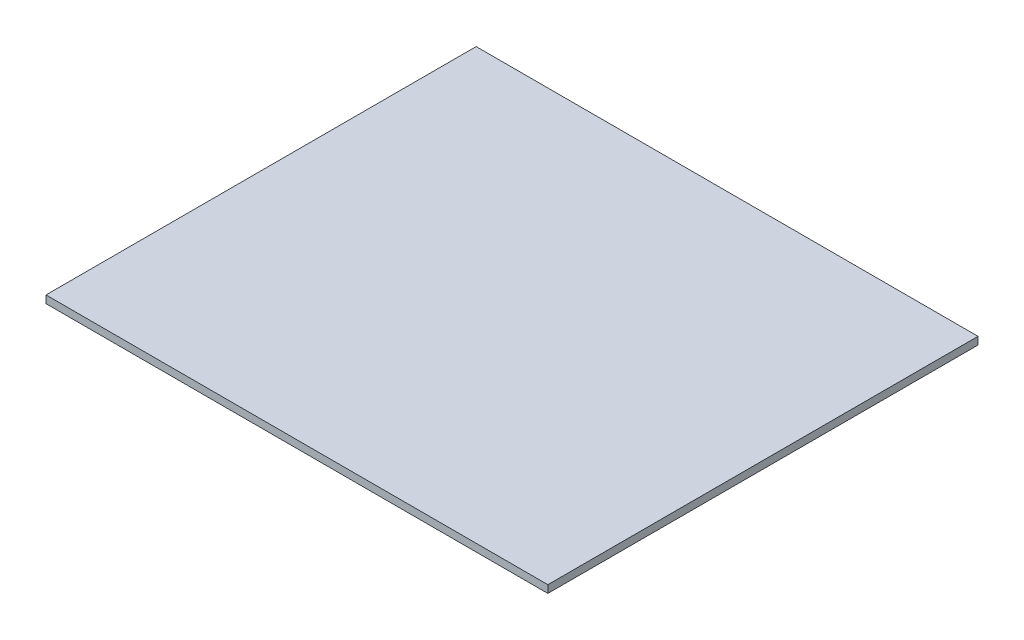
SolidWorks part; units mm, degrees
ref_plane "Front" through (0, 0, 0) normal (0, 0, 1) x (1, 0, 0)
ref_plane "Top" through (0, 0, 0) normal (0, 1, 0) x (1, 0, 0)
ref_plane "Right" through (0, 0, 0) normal (1, 0, 0) x (0, 0, -1)
sketch "Croquis1" plane through (0, 0, 0) normal (0, 1, 0) x (1, 0, 0)
  line L1 (0, 0) -> (210, 0)
  line L2 (0, 0) -> (0, 180)
  line L3 (0, 180) -> (210, 180)
  line L4 (210, 0) -> (210, 180)
  dimension "D1" = 210
  dimension "D2" = 180
extrude "Saliente-Extruir1" add sketch "Croquis1" along normal blind 3.175
